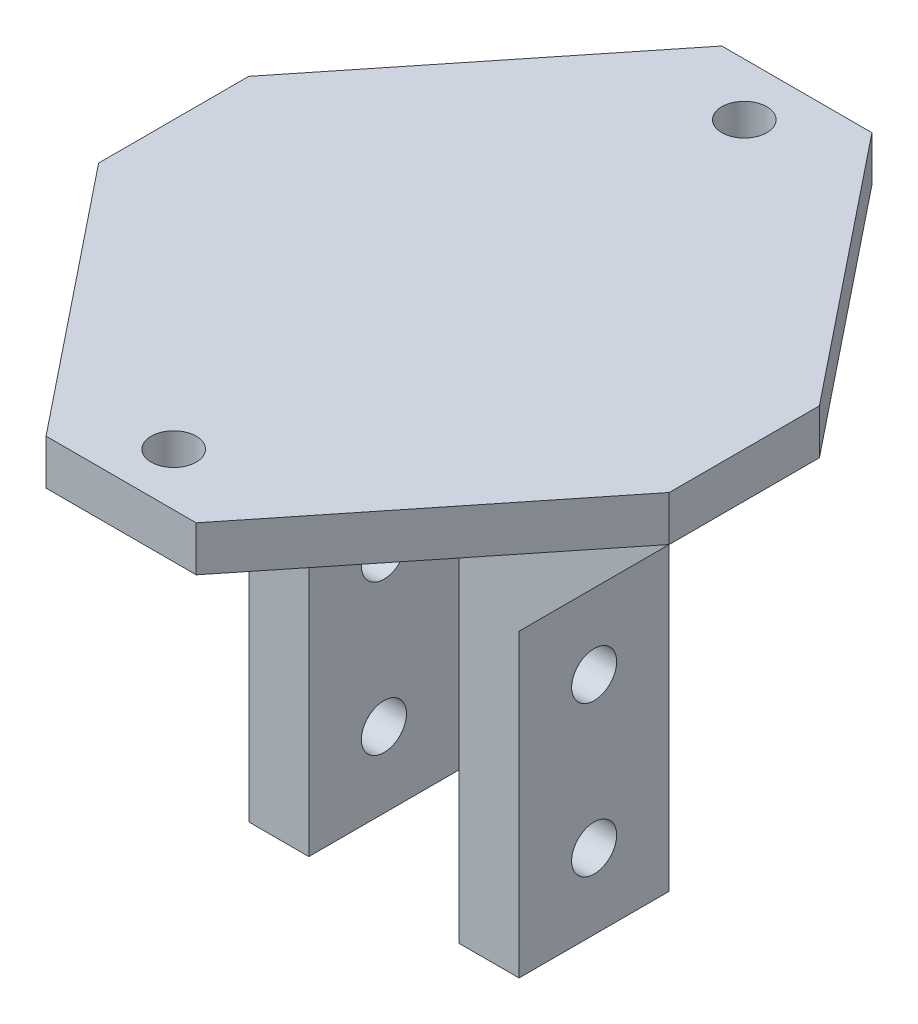
SolidWorks part; units mm, degrees
ref_plane "前视基准面" through (0, 0, 0) normal (0, 0, 1) x (1, 0, 0)
ref_plane "上视基准面" through (0, 0, 0) normal (0, 1, 0) x (1, 0, 0)
ref_plane "右视基准面" through (0, 0, 0) normal (1, 0, 0) x (0, 0, -1)
sketch "草图1" plane through (0, 0, 0) normal (0, 1, 0) x (1, 0, 0)
  line L1 (-19, 22.5) -> (19, 22.5)
  line L2 (-19, 22.5) -> (-19, -22.5)
  line L3 (-19, -22.5) -> (19, -22.5)
  line L4 (19, 22.5) -> (19, -22.5)
  line L5 (-19, 22.5) -> (19, -22.5) construction
  line L6 (-19, -22.5) -> (19, 22.5) construction
  point P0 (0, 0)
extrude "凸台-拉伸1" add sketch "草图1" along normal blind 3
sketch "草图2" plane through (0, 0, 0) normal (0, -1, 0) x (-1, 0, 0)
  line L1 (5, -5) -> (-5, -5)
  line L2 (5, -5) -> (5, 5)
  line L3 (5, 5) -> (-5, 5)
  line L4 (-5, -5) -> (-5, 5)
  line L5 (5, -5) -> (-5, 5) construction
  line L6 (5, 5) -> (-5, -5) construction
  line L7 (-19, -22.5) -> (-19, 22.5) construction
  line L8 (-19, -5) -> (-19, 5)
  line L11 (19, 22.5) -> (19, -22.5) construction
  line L12 (19, 5) -> (19, -5)
  point P0 (0, 0)
ref_plane "基准面1" through (0, 0, -5) normal (0, 0, -1) x (1, 0, 0)
sketch "草图3" plane through (0, 0, -5) normal (0, 0, -1) x (1, 0, 0)
  line L0 (-5, 0) -> (-5, 30)
  line L1 (-5, 30) -> (-9, 30)
  line L2 (-9, 30) -> (-9, 10)
  line L3 (-9, 10) -> (-19, 0)
  line L4 (-19, 0) -> (-5, 0)
extrude "凸台-拉伸2" add sketch "草图3" against normal blind 10
ref_plane "基准面2" through (0, 0, 0) normal (1, 0, 0) x (0, 0, -1)
mirror "镜向1" about plane through (0, 0, 0) normal (1, 0, 0) of "凸台-拉伸2"
hole_wizard "Ø3.0 (3) 直径孔1" positions "草图5" profile "草图4" hole size "Ø3.0" standard "GB" end condition through all
sketch "草图5" plane through (0, 0, 0) normal (0, -1, 0) x (-1, 0, 0)
  line L0 (0, -19) -> (0, 0)
  line L2 (0, 0) -> (0, 19)
  point P0 (0, -19)
  point P2 (0, 19)
sketch "草图4" plane through (0, 0, 19) normal (1, 0, 0) x (0, 0, -1)
  line L0 (0, 0) -> (0, 3)
  line L1 (0, 3) -> (1.5, 3)
  line L2 (1.5, 3) -> (1.5, 0)
  line L5 (1.5, 0) -> (0, 0)
  line L11 (0, -6.35) -> (0, 107.95) construction
  dimension "通孔孔直径" = 3
  dimension "通孔孔深度" = 3
hole_wizard "Ø3.0 (3) 直径孔2" positions "草图7" profile "草图6" hole size "Ø3.0" standard "GB" end condition through all
sketch "草图7" plane through (9, 0, 0) normal (1, 0, 0) x (0, 0, -1)
  line L0 (0, -25) -> (0, -30)
  line L1 (-5, -30) -> (5, -30) construction
  line L3 (0, -15) -> (0, -10)
  line L4 (-5, -10) -> (5, -10) construction
  point P0 (0, -25)
  point P2 (0, -15)
sketch "草图6" plane through (9, -25, 0) normal (0, 1, 0) x (0, 0, -1)
  line L0 (0, 0) -> (0, 28)
  line L1 (0, 28) -> (1.5, 28)
  line L2 (1.5, 28) -> (1.5, 0)
  line L5 (1.5, 0) -> (0, 0)
  line L11 (0, -6.35) -> (0, 107.95) construction
  dimension "通孔孔直径" = 3
  dimension "通孔孔深度" = 28
sketch "草图8" plane through (0, 0, 0) normal (0, -1, 0) x (-1, 0, 0)
  line L0 (5, -5) -> (5, -22.5)
  line L1 (19, -22.5) -> (-19, -22.5) construction
  line L2 (5, -22.5) -> (19, -5)
  line L3 (19, -5) -> (19, -22.5)
  line L4 (19, -22.5) -> (5, -22.5)
  line M5 (-19, -22.5) -> (19, -22.5)
  line M6 (19, -22.5) -> (19, -5)
extrude "切除-拉伸1" cut sketch "草图8" against normal blind 200 contours L2 M5 M6
mirror "镜向2" about plane through (0, 0, 0) normal (1, 0, 0) of "切除-拉伸1"
ref_plane "基准面3" through (0, 0, 0) normal (0, 0, -1) x (-1, 0, 0)
mirror "镜向3" about plane through (0, 0, 0) normal (0, 0, -1) of "镜向2", "切除-拉伸1"
